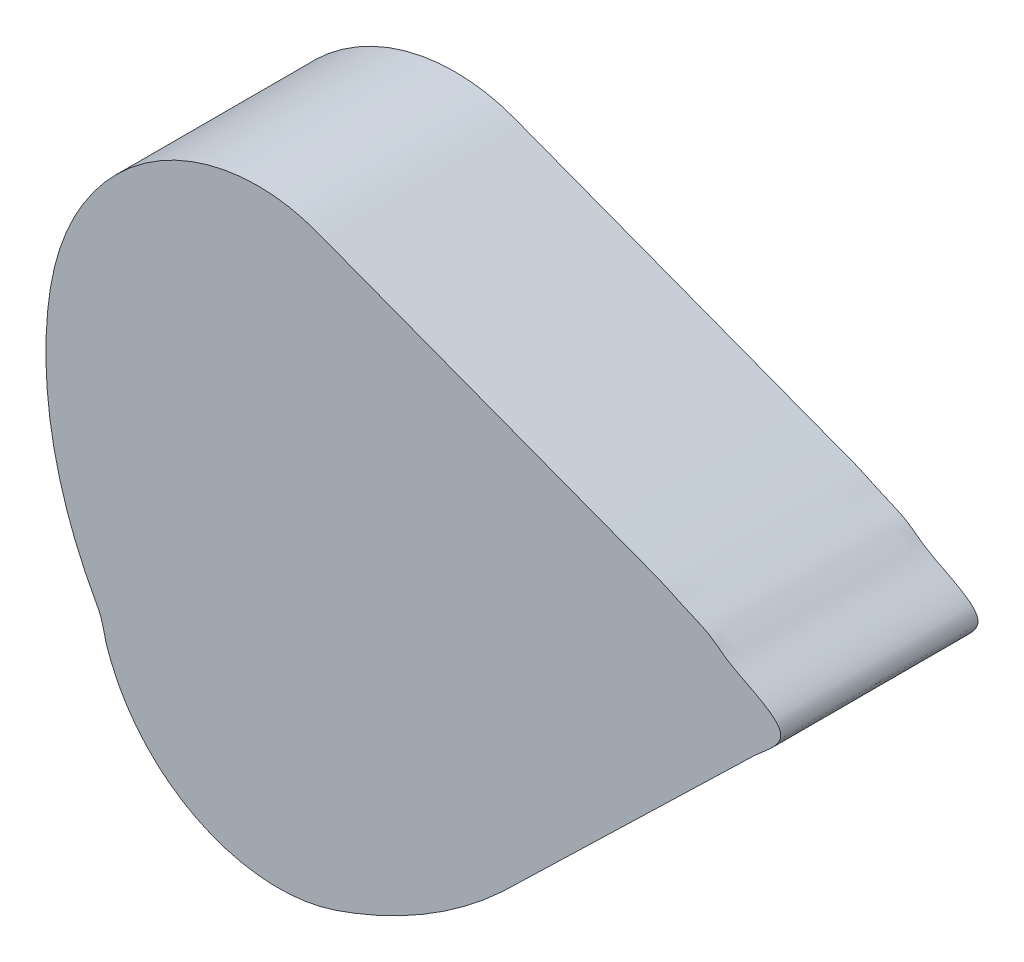
SolidWorks part; units mm, degrees
ref_plane "Front Plane" through (0, 0, 0) normal (0, 0, 1) x (1, 0, 0)
ref_plane "Top Plane" through (0, 0, 0) normal (0, 1, 0) x (1, 0, 0)
ref_plane "Right Plane" through (0, 0, 0) normal (1, 0, 0) x (0, 0, -1)
sketch3d "3DSketch1"
  spline S0 degree 3 poles (19.3169, -1.4231, 0) (21.824, 0.3095, 0) (18.0884, 1.582, 0) (17.049, 2.6243, 0) (15.5584, 3.1863, 0) (14.6373, 3.6821, 0) (13.5265, 4.0582, 0) (12.6297, 4.4209, 0) (11.7187, 4.755, 0) (10.9729, 5.0434, 0) (10.2727, 5.3068, 0) (9.643, 5.5467, 0) (9.0104, 5.7864, 0) (8.442, 6.0022, 0) (7.8732, 6.2179, 0) (7.3678, 6.4097, 0) (6.8623, 6.6015, 0) (6.42, 6.7693, 0) (5.9777, 6.9371, 0) (5.5986, 7.081, 0) (5.2195, 7.2248, 0) (4.8404, 7.3687, 0) (4.4613, 7.5125, 0) (4.0822, 7.6564, 0) (3.7031, 7.8002, 0) (3.324, 7.9441, 0) (2.9449, 8.0879, 0) (2.5658, 8.2318, 0) (2.1867, 8.3756, 0) (1.8075, 8.5194, 0) (1.3653, 8.6873, 0) (0.923, 8.8551, 0) (0.4807, 9.0229, 0) (0.1016, 9.1667, 0) (-0.3407, 9.3346, 0) (-0.783, 9.5024, 0) (-1.2885, 9.6942, 0) (-1.7939, 9.8862, 0) (-2.363, 10.1008, 0) (-2.93, 10.321, 0) (-3.5057, 10.5179, 0) (-4.0964, 10.6657, 0) (-4.6955, 10.772, 0) (-5.3009, 10.8352, 0) (-5.9767, 10.8592, 0) (-6.6525, 10.8299, 0) (-7.3239, 10.7493, 0) (-7.9887, 10.6259, 0) (-8.6429, 10.4541, 0) (-9.2829, 10.2362, 0) (-9.9088, 9.9805, 0) (-10.5157, 9.682, 0) (-11.1594, 9.3094, 0) (-11.7213, 8.9331, 0) (-12.3108, 8.4797, 0) (-12.8697, 7.9888, 0) (-13.44, 7.4115, 0) (-13.9234, 6.8461, 0) (-14.372, 6.253, 0) (-14.7829, 5.633, 0) (-15.1516, 4.987, 0) (-15.4809, 4.3202, 0) (-15.7699, 3.6348, 0) (-16.0343, 2.8677, 0) (-16.2478, 2.0849, 0) (-16.3992, 1.3568, 0) (-16.5145, 0.6222, 0) (-16.5968, -0.1168, 0) (-16.6487, -0.9263, 0) (-16.6687, -1.7372, 0) (-16.6575, -2.5482, 0) (-16.612, -3.3581, 0) (-16.533, -4.1654, 0) (-16.4301, -4.9018, 0) (-16.289, -5.7005, 0) (-16.1151, -6.4928, 0) (-15.8873, -7.3416, 0) (-15.6454, -8.1157, 0) (-15.3726, -8.8797, 0) (-15.0428, -9.6939, 0) (-14.6786, -10.4943, 0) (-14.2784, -11.2753, 0) (-13.8249, -12.0347, 0) (-13.6783, -12.9827, 0) (-13.3249, -13.8628, 0) (-12.9241, -14.7194, 0) (-12.4259, -15.527, 0) (-11.8057, -16.3298, 0) (-11.0969, -17.0576, 0) (-10.3669, -17.6612, 0) (-9.5781, -18.1859, 0) (-8.7429, -18.633, 0) (-7.8624, -18.9838, 0) (-6.9517, -19.2439, 0) (-6.0192, -19.4123, 0) (-5.0062, -19.4819, 0) (-4.0596, -19.4397, 0) (-3.1219, -19.3058, 0) (-2.2027, -19.0752, 0) (-1.2489, -18.7296, 0) (-0.3074, -18.3542, 0) (0.5541, -17.962, 0) (1.4011, -17.5404, 0) (2.171, -17.1167, 0) (2.9243, -16.6644, 0) (3.6046, -16.2227, 0) (4.2692, -15.7577, 0) (4.9173, -15.27, 0) (5.5479, -14.76, 0) (6.1103, -14.2737, 0) (6.6564, -13.7693, 0) (7.1892, -13.2508, 0) (7.7236, -12.7341, 0) (8.2091, -12.2639, 0) (8.6947, -11.7939, 0) (9.1802, -11.3239, 0) (9.7143, -10.8068, 0) (10.1999, -10.3368, 0) (10.6854, -9.8667, 0) (11.171, -9.3967, 0) (11.6565, -8.9266, 0) (12.1906, -8.4096, 0) (12.7247, -7.8926, 0) (13.2589, -7.3755, 0) (13.7928, -6.8585, 0) (14.3274, -6.3413, 0) (14.909, -5.7775, 0) (15.5425, -5.1659, 0) (16.1691, -4.5561, 0) (16.858, -3.8955, 0) (17.5187, -3.2426, 0) (18.3363, -2.4805, 0) (19.3169, -1.4231, 0) (21.824, 0.3095, 0) (18.0884, 1.582, 0) knots -0.044922 -0.035156 -0.023437 0 0.033203 0.044922 0.058594 0.070312 0.080078 0.089844 0.099609 0.107422 0.113281 0.121094 0.126953 0.132813 0.138672 0.144531 0.148438 0.154297 0.158203 0.162109 0.166016 0.169922 0.173828 0.177734 0.181641 0.185547 0.189453 0.193359 0.197266 0.201172 0.205078 0.210937 0.214844 0.21875 0.222656 0.228516 0.232422 0.238281 0.244141 0.25 0.255859 0.261719 0.267578 0.273438 0.279297 0.287109 0.292969 0.298828 0.306641 0.3125 0.318359 0.326172 0.332031 0.339844 0.345703 0.353516 0.361328 0.369141 0.375 0.382812 0.390625 0.396484 0.404297 0.412109 0.419922 0.427734 0.433594 0.441406 0.449219 0.457031 0.464844 0.472656 0.480469 0.488281 0.494141 0.503906 0.511719 0.519531 0.527344 0.535156 0.544922 0.552734 0.560547 0.570312 0.580078 0.587891 0.597656 0.607422 0.617187 0.626953 0.634766 0.644531 0.654297 0.662109 0.671875 0.681641 0.691406 0.699219 0.708984 0.71875 0.728516 0.738281 0.746094 0.755859 0.763672 0.771484 0.779297 0.787109 0.794922 0.802734 0.808594 0.816406 0.824219 0.830078 0.835938 0.84375 0.849609 0.857422 0.863281 0.869141 0.876953 0.882812 0.890625 0.898438 0.904297 0.912109 0.919922 0.927734 0.9375 0.945312 0.955078 0.964844 0.976563 1 1.033203 1.044922 1.058594 only from (20.5802, -0.0033, 0) to (20.5802, -0.0033, 0)
extrude "Boss-Extrude1" add sketch "3DSketch1" along direction (0, 0, 1) on the side of the normal blind 10
